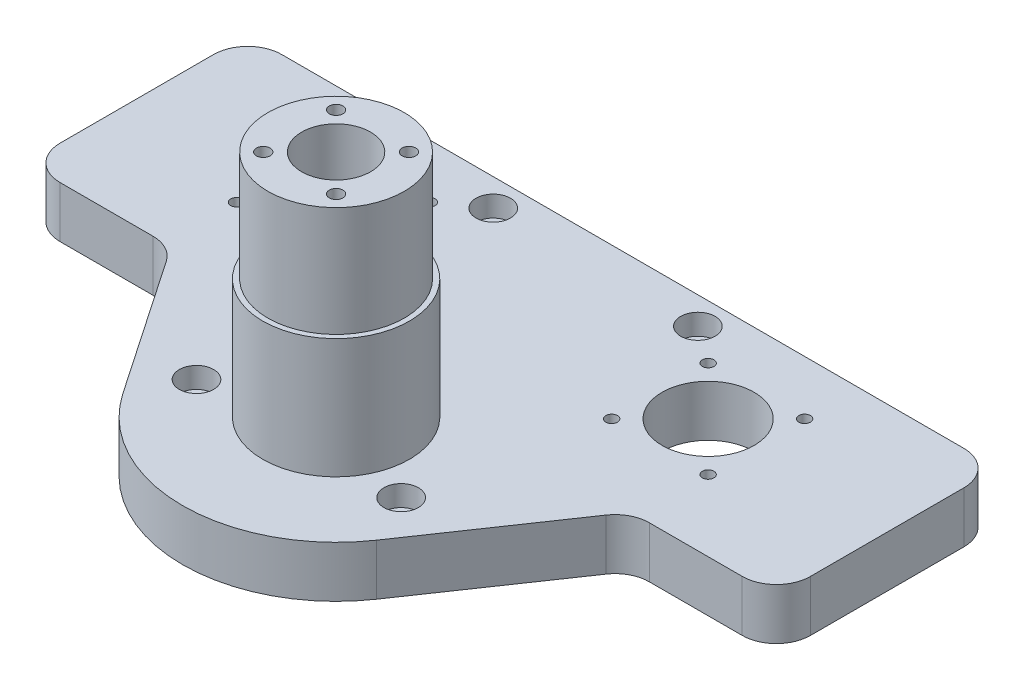
SolidWorks part; units mm, degrees
material "PLA Infill"
ref_plane "Front Plane" through (0, 0, 0) normal (0, 0, 1) x (1, 0, 0)
ref_plane "Top Plane" through (0, 0, 0) normal (0, 1, 0) x (1, 0, 0)
ref_plane "Right Plane" through (0, 0, 0) normal (1, 0, 0) x (0, 0, -1)
sketch "Sketch1" plane through (0, 0, 0) normal (0, 1, 0) x (1, 0, 0)
  line L0 (0, 0) -> (55, 54.0672) construction
  line L1 (55, 54.0672) -> (-55, 54.0672) construction
  line L2 (-55, 54.0672) -> (0, 0) construction
  line L3 (-79.7903, 37.1722) -> (-37.1854, -25.3425) construction
  line L4 (-55, 84.0672) -> (55, 84.0672)
  line L5 (37.1854, -25.3425) -> (79.7903, 37.1722) construction
  line L6 (-55, 84.0672) -> (-100, 84.0672)
  line L7 (-110, 74.0672) -> (-110, 29.0672)
  line L8 (-100, 19.0672) -> (-72.7378, 19.0672)
  line L9 (-64.4743, 14.6989) -> (-37.1854, -25.3425)
  line L10 (0, -1000) -> (0, 49000) construction
  line L11 (64.4743, 14.6989) -> (37.1854, -25.3425)
  line L12 (100, 19.0672) -> (72.7378, 19.0672)
  line L13 (110, 74.0672) -> (110, 29.0672)
  line L14 (55, 84.0672) -> (100, 84.0672)
  circle A0 centre (-55, 54.0672) radius 30 construction
  circle A1 centre (55, 54.0672) radius 30 construction
  circle A2 centre (0, 0) radius 45 construction
  arc A3 (-79.7903, 37.1722) -> (-55, 84.0672) centre (-55, 54.0672) cw construction
  arc A4 (55, 84.0672) -> (79.7903, 37.1722) centre (55, 54.0672) cw construction
  arc A5 (-37.1854, -25.3425) -> (37.1854, -25.3425) centre (0, 0) ccw
  arc A6 (-72.7378, 19.0672) -> (-64.4743, 14.6989) centre (-72.7378, 9.0672) cw
  arc A7 (-110, 29.0672) -> (-100, 19.0672) centre (-100, 29.0672) ccw
  arc A8 (-100, 84.0672) -> (-110, 74.0672) centre (-100, 74.0672) ccw
  arc A9 (72.7378, 19.0672) -> (64.4743, 14.6989) centre (72.7378, 9.0672) ccw
  arc A10 (110, 29.0672) -> (100, 19.0672) centre (100, 29.0672) cw
  arc A11 (100, 84.0672) -> (110, 74.0672) centre (100, 74.0672) cw
  point P23 (-67.4514, 19.0672)
  dimension "D3" = 60
  dimension "D4" = 90
  dimension "D5" = 10
  dimension "D6" = 55
  dimension "D1" = 110
  dimension "D2" = 77.125
  dimension "D7" = 35
extrude "Main Body" add sketch "Sketch1" along normal blind 15
sketch "Sketch3" plane through (0, 15, 0) normal (0, 1, 0) x (1, 0, 0)
  circle A0 centre (0, 0) radius 45 construction
  circle A1 centre (0, 0) radius 45 construction
  circle A2 centre (0, 0) radius 21.5
  dimension "D1" = 43
extrude "Front Extrusion" add sketch "Sketch3" along normal blind 67.3
sketch "Sketch4" plane through (0, 0, 0) normal (0, -1, 0) x (1, 0, 0)
  line L0 (0, -1000) -> (0, 49000) construction
  line L1 (-45, 0) -> (45, 0) construction
  line L2 (-85, -54.0672) -> (-25, -54.0672) construction
  line L3 (55, -54.0672) -> (-55, -54.0672) construction
  line L4 (-55, -24.0672) -> (-55, -84.0672) construction
  line L5 (-10.6773, 10.6773) -> (0, 0) construction
  line L6 (-10.6773, -10.6773) -> (0, 0) construction
  line L7 (-69.1421, -39.9251) -> (-55, -54.0672) construction
  line L8 (-100, -84.0672) -> (100, -84.0672) construction
  line L9 (100, -84.0672) -> (-100, -84.0672) construction
  line L10 (-30, -76.0672) -> (0, -76.0672) construction
  line L11 (-30, -76.0672) -> (-30, 10.9328) construction
  line L12 (-30, 10.9328) -> (0, 10.9328) construction
  line L13 (0, -76.0672) -> (0, 10.9328) construction
  circle A0 centre (55, -54.0672) radius 30 construction
  circle A1 centre (0, 0) radius 45 construction
  circle A2 centre (-55, -54.0672) radius 30 construction
  circle A3 centre (55, -54.0672) radius 30 construction
  circle A4 centre (0, 0) radius 45 construction
  circle A5 centre (-55, -54.0672) radius 30 construction
  circle A6 centre (0, 0) radius 10.1
  circle A7 centre (-55, -54.0672) radius 13.5
  circle A10 centre (-10.6773, 10.6773) radius 2
  circle A13 centre (-10.6773, -10.6773) radius 2
  circle A14 centre (-69.1421, -39.9251) radius 1.7
  circle A15 centre (-69.1421, -68.2094) radius 1.7
  circle A16 centre (-40.8579, -68.2094) radius 1.7
  circle A17 centre (-40.8579, -39.9251) radius 1.7
  circle A18 centre (55, -54.0672) radius 13.5
  circle A19 centre (69.1421, -68.2094) radius 1.7
  circle A20 centre (40.8579, -68.2094) radius 1.7
  circle A21 centre (40.8579, -39.9251) radius 1.7
  circle A22 centre (69.1421, -39.9251) radius 1.7
  circle A23 centre (10.6773, -10.6773) radius 2
  circle A24 centre (10.6773, 10.6773) radius 2
  circle A25 centre (-30, -76.0672) radius 3
  circle A26 centre (-30, 10.9328) radius 3
  circle A27 centre (30, -76.0672) radius 3
  circle A28 centre (30, 10.9328) radius 3
  dimension "D1" = 20.2
  dimension "D2" = 27
  dimension "D4" = 4
  dimension "D5" = 45
  dimension "D7" = 3.4
  dimension "D9" = 6
  dimension "D3" = 15.1
  dimension "D6" = 20
  dimension "D8" = 45
  dimension "D10" = 30
  dimension "D11" = 8
  dimension "D12" = 87
extrude "Bolt Holes" cut sketch "Sketch4" against normal through all
sketch "Sketch5" plane through (0, 0, 0) normal (0, -1, 0) x (1, 0, 0)
  line L0 (-14.92, 6.4347) -> (-9.9876, 1.5024)
  line L1 (-6.4347, 14.92) -> (-1.5024, 9.9876)
  line L2 (-10.6773, 10.6773) -> (0, 0) construction
  line L3 (-1000, 0) -> (49000, 0) construction
  line L4 (0, -1000) -> (0, 49000) construction
  line L5 (-14.92, -6.4347) -> (-9.9876, -1.5024)
  line L6 (-6.4347, -14.92) -> (-1.5024, -9.9876)
  line L7 (6.4347, -14.92) -> (1.5024, -9.9876)
  line L8 (14.92, -6.4347) -> (9.9876, -1.5024)
  line L9 (14.92, 6.4347) -> (9.9876, 1.5024)
  line L10 (6.4347, 14.92) -> (1.5024, 9.9876)
  circle A0 centre (-10.6773, 10.6773) radius 2 construction
  circle A1 centre (-10.6773, 10.6773) radius 6 construction
  circle A2 centre (0, 0) radius 10.1 construction
  arc A3 (-14.92, 6.4347) -> (-6.4347, 14.92) centre (-10.6773, 10.6773) cw
  circle A4 centre (0, 0) radius 10.1 construction
  arc A5 (-9.9876, 1.5024) -> (-1.5024, 9.9876) centre (0, 0) cw
  arc A6 (-14.92, -6.4347) -> (-6.4347, -14.92) centre (-10.6773, -10.6773) ccw
  arc A7 (-9.9876, -1.5024) -> (-1.5024, -9.9876) centre (0, 0) ccw
  arc A8 (14.92, -6.4347) -> (6.4347, -14.92) centre (10.6773, -10.6773) cw
  arc A9 (9.9876, -1.5024) -> (1.5024, -9.9876) centre (0, 0) cw
  arc A10 (14.92, 6.4347) -> (6.4347, 14.92) centre (10.6773, 10.6773) ccw
  arc A11 (9.9876, 1.5024) -> (1.5024, 9.9876) centre (0, 0) ccw
  dimension "D1" = 4
  dimension "D2" = 4
extrude "Bolt Recesses Rear" cut sketch "Sketch5" against normal blind 10
sketch "Sketch6" plane through (0, 15, 0) normal (0, 1, 0) x (1, 0, 0)
  circle A1 centre (30, 76.0672) radius 5.05
  circle A2 centre (-30, -10.9328) radius 3 construction
  circle A3 centre (30, -10.9328) radius 3 construction
  circle A4 centre (30, 76.0672) radius 3 construction
  circle A5 centre (-30, 76.0672) radius 3 construction
  circle A6 centre (-30, -10.9328) radius 3 construction
  circle A7 centre (30, -10.9328) radius 3 construction
  circle A8 centre (30, 76.0672) radius 3 construction
  circle A9 centre (-30, 76.0672) radius 3 construction
  circle A10 centre (-30, 76.0672) radius 5.05
  circle A11 centre (-30, -10.9328) radius 5.05
  circle A12 centre (30, -10.9328) radius 5.05
  dimension "D1" = 10.1
extrude "Bolt Recesses Front" cut sketch "Sketch6" against normal blind 6.1
ref_plane "First Bearing Section" through (0, 50.1, 0) normal (0, 1, 0) x (1, 0, 0)
sketch "Sketch7" plane through (0, 82.3, 0) normal (0, 1, 0) x (1, 0, 0)
  circle A0 centre (0, 0) radius 21.5 construction
  circle A1 centre (0, 0) radius 21.5
  circle A2 centre (0, 0) radius 20
  dimension "D1" = 40
extrude "Cut-Extrude1" cut sketch "Sketch7" against normal up to surface (32.2 mm away)
sketch "Sketch8" plane through (0, 0, 0) normal (0, -1, 0) x (1, 0, 0)
  line L0 (0, -1000) -> (0, 49000) construction
  circle A0 centre (-69.1421, -68.2094) radius 1.7 construction
  circle A1 centre (-40.8579, -68.2094) radius 1.7 construction
  circle A2 centre (-40.8579, -39.9251) radius 1.7 construction
  circle A3 centre (-69.1421, -39.9251) radius 1.7 construction
  circle A4 centre (-69.1421, -68.2094) radius 1.7 construction
  circle A5 centre (-40.8579, -68.2094) radius 1.7 construction
  circle A6 centre (-40.8579, -39.9251) radius 1.7 construction
  circle A7 centre (-69.1421, -39.9251) radius 1.7 construction
  circle A8 centre (-69.1421, -39.9251) radius 2.85
  circle A9 centre (-40.8579, -39.9251) radius 2.85
  circle A10 centre (-40.8579, -68.2094) radius 2.85
  circle A11 centre (-69.1421, -68.2094) radius 2.85
  circle A12 centre (40.8579, -68.2094) radius 2.85
  circle A13 centre (40.8579, -39.9251) radius 2.85
  circle A14 centre (69.1421, -68.2094) radius 2.85
  circle A15 centre (69.1421, -39.9251) radius 2.85
  dimension "D1" = 5.7
extrude "Motor bolt head recesses" cut sketch "Sketch8" against normal blind 6
sketch "Sketch9" plane through (0, 0, 0) normal (0, -1, 0) x (1, 0, 0)
  line L0 (0, -1000) -> (0, 49000) construction
  line L1 (-110, -74.0672) -> (-110, -29.0672) construction
  line L2 (100, -84.0672) -> (-100, -84.0672) construction
  line L4 (-106, -74.0672) -> (-44, -74.0672) construction
  line L5 (-106, -74.0672) -> (-106, -32.0672) construction
  line L6 (-106, -32.0672) -> (-44, -32.0672) construction
  line L7 (-44, -74.0672) -> (-44, -32.0672) construction
  circle A0 centre (-106, -74.0672) radius 2
  circle A1 centre (-106, -32.0672) radius 2
  circle A2 centre (-44, -32.0672) radius 2
  circle A3 centre (-44, -74.0672) radius 2
  circle A4 centre (44, -74.0672) radius 2
  circle A5 centre (106, -74.0672) radius 2
  circle A6 centre (44, -32.0672) radius 2
  circle A7 centre (106, -32.0672) radius 2
  dimension "D3" = 4
  dimension "D1" = 4
  dimension "D2" = 10
  dimension "D4" = 62
  dimension "D5" = 42
extrude "Heat-set insert holes" cut sketch "Sketch9" against normal blind 6
sketch "Sketch10" plane through (0, 0, 0) normal (0, -1, 0) x (1, 0, 0)
  line L0 (0, -1000) -> (0, 49000) construction
  line L1 (-110, -74.0672) -> (-110, -29.0672) construction
  line L2 (100, -84.0672) -> (-100, -84.0672) construction
  line L4 (-95, -72.0672) -> (-55, -72.0672) construction
  line L5 (-95, -72.0672) -> (-95, -34.0672) construction
  line L6 (-95, -34.0672) -> (-55, -34.0672) construction
  line L7 (-55, -72.0672) -> (-55, -34.0672) construction
  circle A0 centre (-95, -72.0672) radius 1.6
  circle A1 centre (-95, -34.0672) radius 1.6
  circle A2 centre (-55, -34.0672) radius 1.6
  circle A3 centre (-55, -72.0672) radius 1.6
  circle A4 centre (95, -72.0672) radius 1.6
  circle A5 centre (55, -72.0672) radius 1.6
  circle A6 centre (55, -34.0672) radius 1.6
  circle A7 centre (95, -34.0672) radius 1.6
  dimension "D1" = 3.2
  dimension "D2" = 15
  dimension "D3" = 12
  dimension "D4" = 40
  dimension "D5" = 38
extrude "PCB Heat-set insert holes" cut sketch "Sketch10" against normal blind 4
